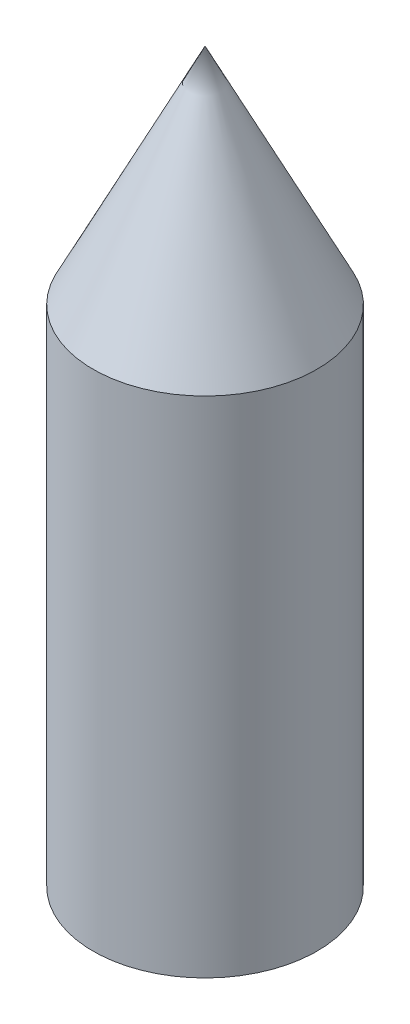
SolidWorks part; units mm, degrees
ref_plane "Plano frontal" through (0, 0, 0) normal (0, 0, 1) x (1, 0, 0)
ref_plane "Plano superior" through (0, 0, 0) normal (0, 1, 0) x (1, 0, 0)
ref_plane "Plano direito" through (0, 0, 0) normal (1, 0, 0) x (0, 0, -1)
sketch "Esboço1" plane through (0, 0, 0) normal (0, 0, 1) x (1, 0, 0)
  line L0 (0, 0) -> (0, 130)
  line L1 (0, 130) -> (20, 90)
  line L2 (20, 90) -> (20, 0)
  line L3 (20, 0) -> (0, 0)
  dimension "D1" = 20
  dimension "D2" = 90
  dimension "D3" = 40
revolve "Revolução1" add sketch "Esboço1" angle 360 about L0
